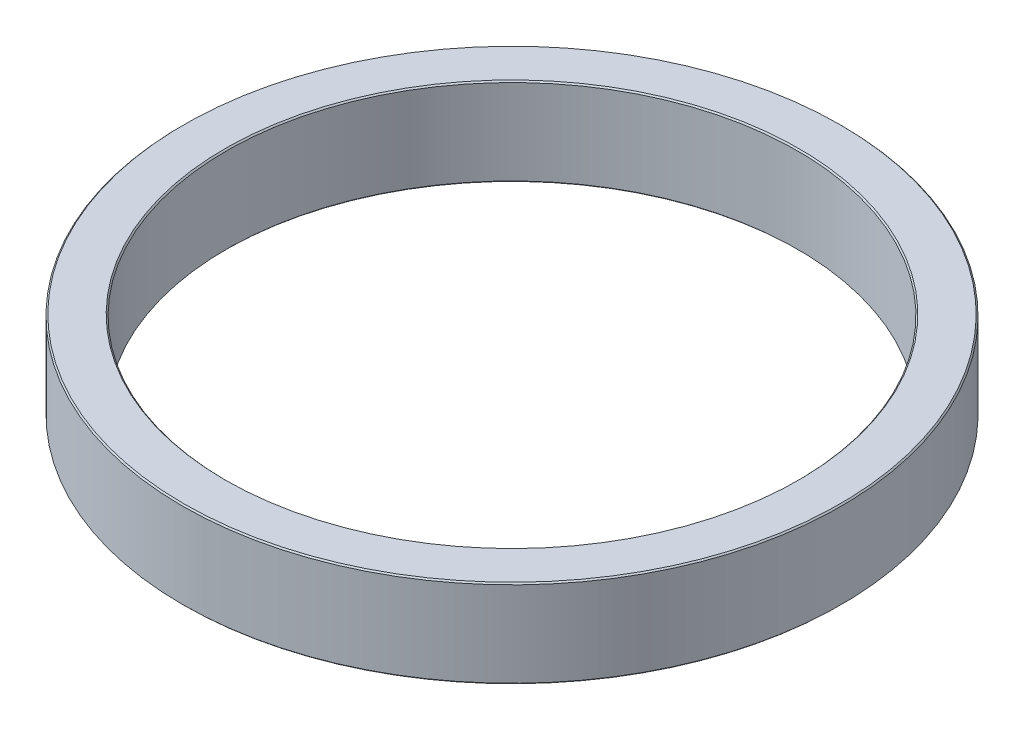
SolidWorks part; units mm, degrees
ref_plane "Front Plane" through (0, 0, 0) normal (0, 0, 1) x (1, 0, 0)
ref_plane "Top Plane" through (0, 0, 0) normal (0, 1, 0) x (1, 0, 0)
ref_plane "Right Plane" through (0, 0, 0) normal (1, 0, 0) x (0, 0, -1)
sketch "Sketch1" plane through (0, 0, 0) normal (0, 1, 0) x (1, 0, 0)
  circle A0 centre (0, 0) radius 32.5
  circle A1 centre (0, 0) radius 37.495
  dimension "D1" = 74.99
  dimension "D2" = 65
extrude "Boss-Extrude1" add sketch "Sketch1" along normal blind 10
chamfer "Chamfer1" distance 0.15 angle 45 4 edges at (0, 0, 37.495) (0, 10, 37.495) (0, 0, 32.5) (0, 10, 32.5)
